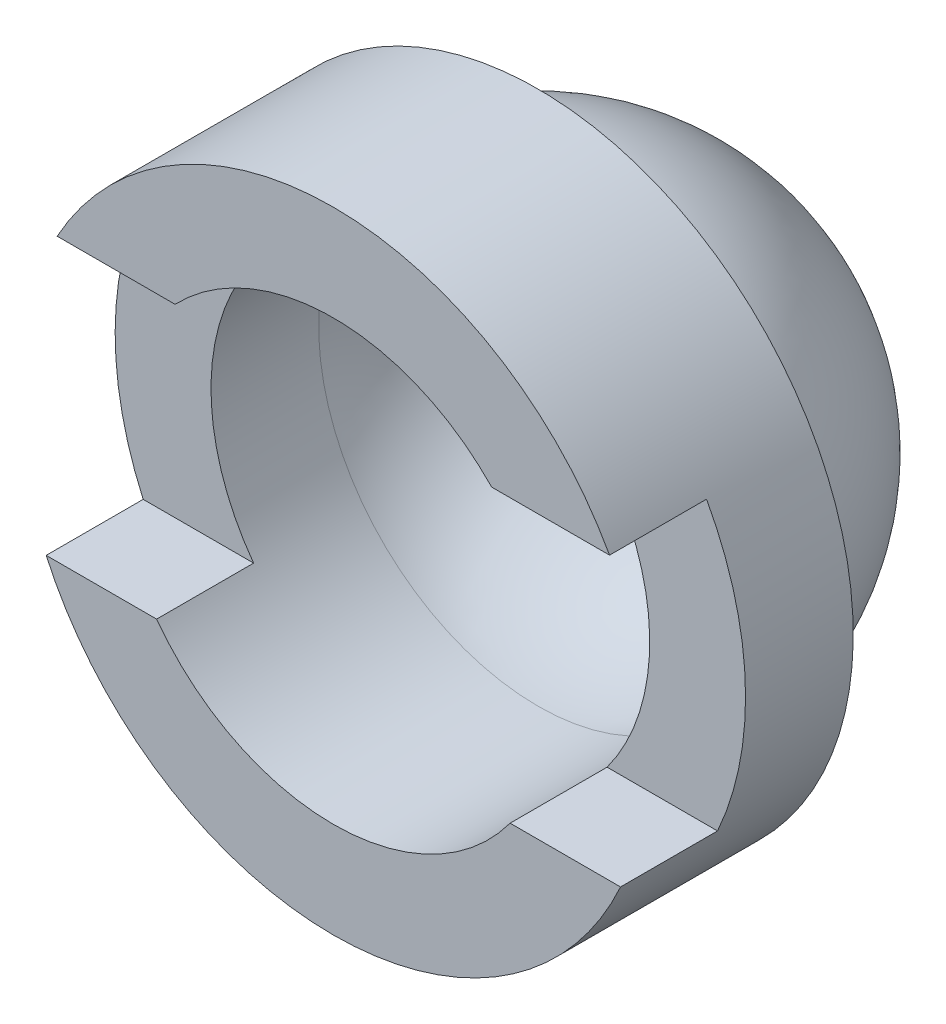
SolidWorks part; units mm, degrees
material "Acrílico (médio-alto impacto)"
ref_plane "Plano frontal" through (0, 0, 0) normal (0, 0, 1) x (1, 0, 0)
ref_plane "Plano superior" through (0, 0, 0) normal (0, 1, 0) x (1, 0, 0)
ref_plane "Plano direito" through (0, 0, 0) normal (1, 0, 0) x (0, 0, -1)
sketch "Esboço1" plane through (0, 0, 0) normal (1, 0, 0) x (0, 0, -1)
  line L7 (4.2204, 6.5) -> (0, 6.5)
  line L11 (4.2204, 6.5) -> (4.2204, 0) construction
  line L13 (4.2204, 5.2796) -> (4.2204, 6.5)
  line L18 (8.7441, 0) -> (9.5, 0)
  line L19 (4.2204, 4.5237) -> (3.4443, 4.5237)
  line L21 (0, 6.5) -> (0, 5.9317)
  line L23 (0, 0) -> (9.5, 0) construction
  line L24 (0, 6.5) -> (0, 0) construction
  line L25 (3.4443, 4.5237) -> (0, 4.5237)
  line L26 (0, 4.5237) -> (0, 5.9317)
  arc A2 (4.2204, 5.2796) -> (9.5, 0) centre (4.2204, 0) cw
  arc A4 (4.2204, 4.5237) -> (8.7441, 0) centre (4.2204, 0) cw
revolve "Revolução1" add sketch "Esboço1" angle 360 about L23
sketch "Esboço2" plane through (0, 0, 0) normal (0, 0, 1) x (1, 0, 0)
  line L1 (-7.9349, 3.1322) -> (8.0567, 3.1322)
  line L2 (-7.9349, 3.1322) -> (-7.9349, -2.6798)
  line L3 (-7.9349, -2.6798) -> (8.0567, -2.6798)
  line L4 (8.0567, 3.1322) -> (8.0567, -2.6798)
  point P4 (8.0567, -2.6798)
extrude "Corte-extrusão1" cut sketch "Esboço2" against normal blind 2
